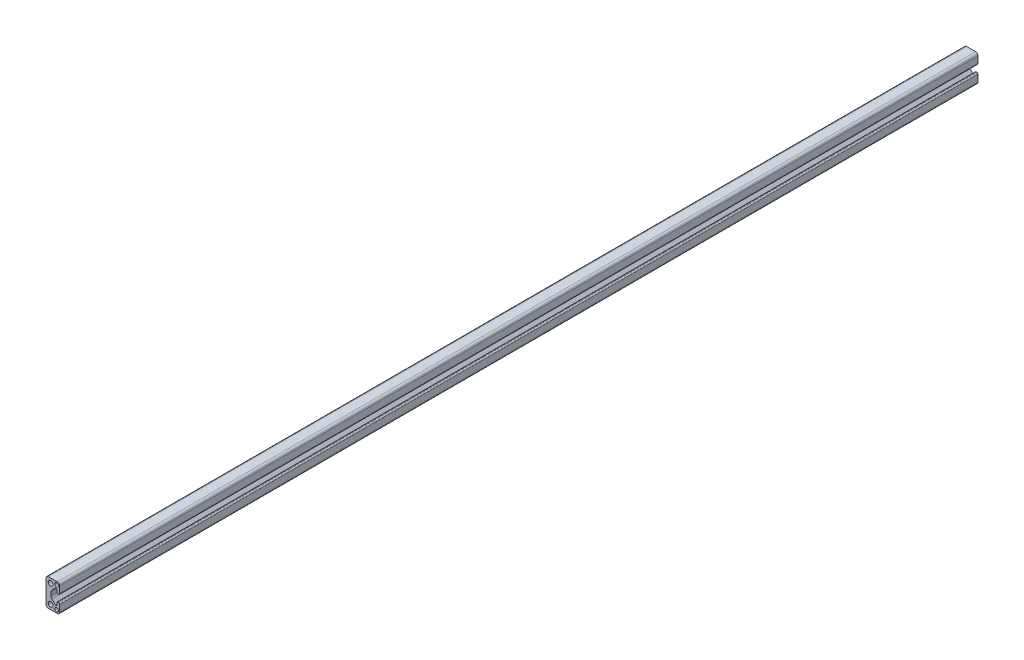
SolidWorks part; units mm, degrees
ref_plane "Front Plane" through (0, 0, 0) normal (0, 0, 1) x (1, 0, 0)
ref_plane "Top Plane" through (0, 0, 0) normal (0, 1, 0) x (1, 0, 0)
ref_plane "Right Plane" through (0, 0, 0) normal (1, 0, 0) x (0, 0, -1)
sketch "Sketch1" plane through (0, 0, 0) normal (0, 0, 1) x (1, 0, 0)
  line L0 (-6.35, 0) -> (6.35, 0) construction
  line L1 (6.35, 4.3011) -> (6.35, 10.5833)
  line L2 (4.2333, 12.7) -> (-4.2333, 12.7)
  line L3 (-6.35, 10.5833) -> (-6.35, 0)
  line L4 (-1.778, 0) -> (-1.778, 1.27)
  line L5 (-0.8467, 3.5339) -> (2.4133, 6.7939)
  line L6 (2.7725, 6.9427) -> (3.048, 6.9427)
  line L7 (3.6407, 6.35) -> (3.6407, 4.3011)
  line L8 (4.6905, 3.2512) -> (5.3001, 3.2512)
  circle A2 centre (3.429, 9.906) radius 1.6933
  circle A3 centre (-2.1167, 8.4667) radius 2.2013
  arc A4 (6.35, 10.5833) -> (4.2333, 12.7) centre (4.2333, 10.5833) ccw
  arc A5 (-4.2333, 12.7) -> (-6.35, 10.5833) centre (-4.2333, 10.5833) ccw
  arc A6 (-0.8467, 3.5339) -> (-1.778, 1.27) centre (1.4393, 1.27) ccw
  arc A7 (2.7725, 6.9427) -> (2.4133, 6.7939) centre (2.7725, 6.4347) ccw
  arc A8 (3.6407, 6.35) -> (3.048, 6.9427) centre (3.048, 6.35) ccw
  arc A9 (3.6407, 4.3011) -> (4.6905, 3.2512) centre (4.6905, 4.3011) ccw
  arc A10 (5.3001, 3.2512) -> (6.35, 4.3011) centre (5.3001, 4.3011) ccw
  dimension "D8" = 2.1167
  dimension "D9" = 3.3867
  dimension "D10" = 4.4027
  dimension "D13" = 1.0499
  dimension "D14" = 3.2173
  dimension "D16" = 0.508
  dimension "D17" = 0.5927
  dimension "Rail Height" = 25.4
  dimension "Rail Width" = 12.7
  dimension "D1" = 4.572
  dimension "D2" = 135
  dimension "D3" = 1.27
  dimension "D4" = 16.9333
  dimension "D5" = 4.2333
  dimension "D7" = 2.921
  dimension "D6" = 19.812
  dimension "TSlot Wdith" = 6.5024
  dimension "D11" = 2.7093
  dimension "D12" = 6.9427
  dimension "D15" = 5.5033
sketch "Sketch2" plane through (0, 0, 0) normal (1, 0, 0) x (0, 0, -1)
  line L0 (-914.4, 0) -> (914.4, 0)
  point P2 (-876.3, 0)
  point P3 (876.3, 0)
  dimension "Length" = 1828.8
  dimension "D1" = 38.1
  dimension "D2" = 38.1
sketch "Sketch3" plane through (0, 0, 0) normal (0, 0, 1) x (1, 0, 0)
  line L0 (-1.778, 0) -> (-1.778, 1.27) construction
  line L1 (-0.8467, 3.5339) -> (2.4133, 6.7939) construction
  line L2 (2.7725, 6.9427) -> (3.048, 6.9427) construction
  line L3 (3.6407, 6.35) -> (3.6407, 4.3011) construction
  line L4 (4.6905, 3.2512) -> (5.3001, 3.2512) construction
  line L5 (6.35, 4.3011) -> (6.35, 10.5833) construction
  line L6 (4.2333, 12.7) -> (-4.2333, 12.7) construction
  line L7 (-6.35, 10.5833) -> (-6.35, 0) construction
  line L8 (-1.778, 0) -> (-1.778, 1.27)
  line L9 (-0.8467, 3.5339) -> (2.4133, 6.7939)
  line L10 (2.7725, 6.9427) -> (3.048, 6.9427)
  line L11 (3.6407, 6.35) -> (3.6407, 4.3011)
  line L12 (4.6905, 3.2512) -> (5.3001, 3.2512)
  line L13 (6.35, 4.3011) -> (6.35, 10.5833)
  line L14 (4.2333, 12.7) -> (-4.2333, 12.7)
  line L15 (-6.35, 10.5833) -> (-6.35, 0)
  line L16 (-6.35, 0) -> (-1.778, 0)
  arc A0 (-0.8467, 3.5339) -> (-1.778, 1.27) centre (1.4393, 1.27) ccw construction
  circle A1 centre (-2.1167, 8.4667) radius 2.2013
  circle A2 centre (-2.1167, 8.4667) radius 2.2013
  circle A3 centre (3.429, 9.906) radius 1.6933
  circle A4 centre (3.429, 9.906) radius 1.6933
  arc A5 (2.7725, 6.9427) -> (2.4133, 6.7939) centre (2.7725, 6.4347) ccw construction
  arc A6 (3.6407, 6.35) -> (3.048, 6.9427) centre (3.048, 6.35) ccw construction
  arc A7 (3.6407, 4.3011) -> (4.6905, 3.2512) centre (4.6905, 4.3011) ccw construction
  arc A8 (5.3001, 3.2512) -> (6.35, 4.3011) centre (5.3001, 4.3011) ccw construction
  arc A9 (6.35, 10.5833) -> (4.2333, 12.7) centre (4.2333, 10.5833) ccw construction
  arc A10 (-4.2333, 12.7) -> (-6.35, 10.5833) centre (-4.2333, 10.5833) ccw construction
  arc A11 (-0.8467, 3.5339) -> (-1.778, 1.27) centre (1.4393, 1.27) ccw
  arc A12 (2.7725, 6.9427) -> (2.4133, 6.7939) centre (2.7725, 6.4347) ccw
  arc A13 (3.6407, 6.35) -> (3.048, 6.9427) centre (3.048, 6.35) ccw
  arc A14 (3.6407, 4.3011) -> (4.6905, 3.2512) centre (4.6905, 4.3011) ccw
  arc A15 (5.3001, 3.2512) -> (6.35, 4.3011) centre (5.3001, 4.3011) ccw
  arc A16 (6.35, 10.5833) -> (4.2333, 12.7) centre (4.2333, 10.5833) ccw
  arc A17 (-4.2333, 12.7) -> (-6.35, 10.5833) centre (-4.2333, 10.5833) ccw
  dimension "D1" = 0
  dimension "D2" = 0
extrude "Boss-Extrude1" add sketch "Sketch3" along normal mid plane 1828.8
mirror "Mirror1" about plane through (0, 0, 0) normal (0, 1, 0) of bodies 104
sketch "Sketch4" plane through (0, 0, 914.4) normal (0, 0, 1) x (1, 0, 0)
  line L14 (-6.35, 10.5833) -> (-6.35, -10.5833)
  line L15 (-4.2333, -12.7) -> (4.2333, -12.7)
  line L16 (6.35, -10.5833) -> (6.35, -4.3011)
  line L17 (5.3001, -3.2512) -> (4.6905, -3.2512)
  line L18 (3.6407, -4.3011) -> (3.6407, -6.35)
  line L19 (3.048, -6.9427) -> (2.7725, -6.9427)
  line L20 (2.4133, -6.7939) -> (-0.8467, -3.5339)
  line L21 (-1.778, -1.27) -> (-1.778, 1.27)
  line L22 (-0.8467, 3.5339) -> (2.4133, 6.7939)
  line L23 (2.7725, 6.9427) -> (3.048, 6.9427)
  line L24 (3.6407, 6.35) -> (3.6407, 4.3011)
  line L25 (4.6905, 3.2512) -> (5.3001, 3.2512)
  line L26 (6.35, 4.3011) -> (6.35, 10.5833)
  line L27 (4.2333, 12.7) -> (-4.2333, 12.7)
  line L28 (-6.35, 10.5833) -> (-6.35, -10.5833)
  line L29 (-4.2333, -12.7) -> (4.2333, -12.7)
  line L30 (6.35, -10.5833) -> (6.35, -4.3011)
  line L31 (5.3001, -3.2512) -> (4.6905, -3.2512)
  line L32 (3.6407, -4.3011) -> (3.6407, -6.35)
  line L33 (3.048, -6.9427) -> (2.7725, -6.9427)
  line L34 (2.4133, -6.7939) -> (-0.8467, -3.5339)
  line L35 (-1.778, -1.27) -> (-1.778, 1.27)
  line L36 (-0.8467, 3.5339) -> (2.4133, 6.7939)
  line L37 (2.7725, 6.9427) -> (3.048, 6.9427)
  line L38 (3.6407, 6.35) -> (3.6407, 4.3011)
  line L39 (4.6905, 3.2512) -> (5.3001, 3.2512)
  line L40 (6.35, 4.3011) -> (6.35, 10.5833)
  line L41 (4.2333, 12.7) -> (-4.2333, 12.7)
  arc A14 (-6.35, -10.5833) -> (-4.2333, -12.7) centre (-4.2333, -10.5833) ccw
  arc A15 (4.2333, -12.7) -> (6.35, -10.5833) centre (4.2333, -10.5833) ccw
  arc A16 (6.35, -4.3011) -> (5.3001, -3.2512) centre (5.3001, -4.3011) ccw
  arc A17 (4.6905, -3.2512) -> (3.6407, -4.3011) centre (4.6905, -4.3011) ccw
  arc A18 (3.048, -6.9427) -> (3.6407, -6.35) centre (3.048, -6.35) ccw
  arc A19 (2.4133, -6.7939) -> (2.7725, -6.9427) centre (2.7725, -6.4347) ccw
  arc A20 (-1.778, -1.27) -> (-0.8467, -3.5339) centre (1.4393, -1.27) ccw
  arc A21 (-0.8467, 3.5339) -> (-1.778, 1.27) centre (1.4393, 1.27) ccw
  arc A22 (2.7725, 6.9427) -> (2.4133, 6.7939) centre (2.7725, 6.4347) ccw
  arc A23 (3.6407, 6.35) -> (3.048, 6.9427) centre (3.048, 6.35) ccw
  arc A24 (3.6407, 4.3011) -> (4.6905, 3.2512) centre (4.6905, 4.3011) ccw
  arc A25 (5.3001, 3.2512) -> (6.35, 4.3011) centre (5.3001, 4.3011) ccw
  arc A26 (6.35, 10.5833) -> (4.2333, 12.7) centre (4.2333, 10.5833) ccw
  arc A27 (-4.2333, 12.7) -> (-6.35, 10.5833) centre (-4.2333, 10.5833) ccw
  arc A28 (-6.35, -10.5833) -> (-4.2333, -12.7) centre (-4.2333, -10.5833) ccw
  arc A29 (4.2333, -12.7) -> (6.35, -10.5833) centre (4.2333, -10.5833) ccw
  arc A30 (6.35, -4.3011) -> (5.3001, -3.2512) centre (5.3001, -4.3011) ccw
  arc A31 (4.6905, -3.2512) -> (3.6407, -4.3011) centre (4.6905, -4.3011) ccw
  arc A32 (3.048, -6.9427) -> (3.6407, -6.35) centre (3.048, -6.35) ccw
  arc A33 (2.4133, -6.7939) -> (2.7725, -6.9427) centre (2.7725, -6.4347) ccw
  arc A34 (-1.778, -1.27) -> (-0.8467, -3.5339) centre (1.4393, -1.27) ccw
  arc A35 (-0.8467, 3.5339) -> (-1.778, 1.27) centre (1.4393, 1.27) ccw
  arc A36 (2.7725, 6.9427) -> (2.4133, 6.7939) centre (2.7725, 6.4347) ccw
  arc A37 (3.6407, 6.35) -> (3.048, 6.9427) centre (3.048, 6.35) ccw
  arc A38 (3.6407, 4.3011) -> (4.6905, 3.2512) centre (4.6905, 4.3011) ccw
  arc A39 (5.3001, 3.2512) -> (6.35, 4.3011) centre (5.3001, 4.3011) ccw
  arc A40 (6.35, 10.5833) -> (4.2333, 12.7) centre (4.2333, 10.5833) ccw
  arc A41 (-4.2333, 12.7) -> (-6.35, 10.5833) centre (-4.2333, 10.5833) ccw
  dimension "D1" = 0
extrude "Cut-Extrude1" cut sketch "Sketch4" against normal blind 977.9
equation "\"D1@Sketch1\"=\"Rail Width@Sketch1\"*0.36"
equation "\"D3@Sketch1\"=\"Rail Height@Sketch1\"*0.05"
equation "\"D4@Sketch1\"=\"Rail Height@Sketch1\"*2/3"
equation "\"D5@Sketch1\"=\"D4@Sketch1\"*1/4"
equation "\"D7@Sketch1\"=\"Rail Width@Sketch1\"*0.23"
equation "\"D6@Sketch1\"=\"Rail Height@Sketch1\"*0.78"
equation "\"D8@Sketch1\"=\"D4@Sketch1\"*1/8"
equation "\"D9@Sketch1\"=\"D4@Sketch1\"*1/5"
equation "\"D10@Sketch1\"=\"D4@Sketch1\"*0.26"
equation "\"D11@Sketch1\"=\"D4@Sketch1\"*0.16"
equation "\"D12@Sketch1\"=\"D4@Sketch1\"*0.41"
equation "\"D13@Sketch1\"=\"D4@Sketch1\"*0.062"
equation "\"D14@Sketch1\"=\"D9@Sketch1\"*0.95"
equation "\"D15@Sketch1\"=\"D4@Sketch1\"*0.325"
equation "\"D16@Sketch1\"=\"D4@Sketch1\"*0.03"
equation "\"D17@Sketch1\"=\"D4@Sketch1\"*0.035"
equation "\"D2@Sketch2\"=\"D1@Sketch2\""
equation "\"D1@Boss-Extrude1\"=\"length@sketch2\""
